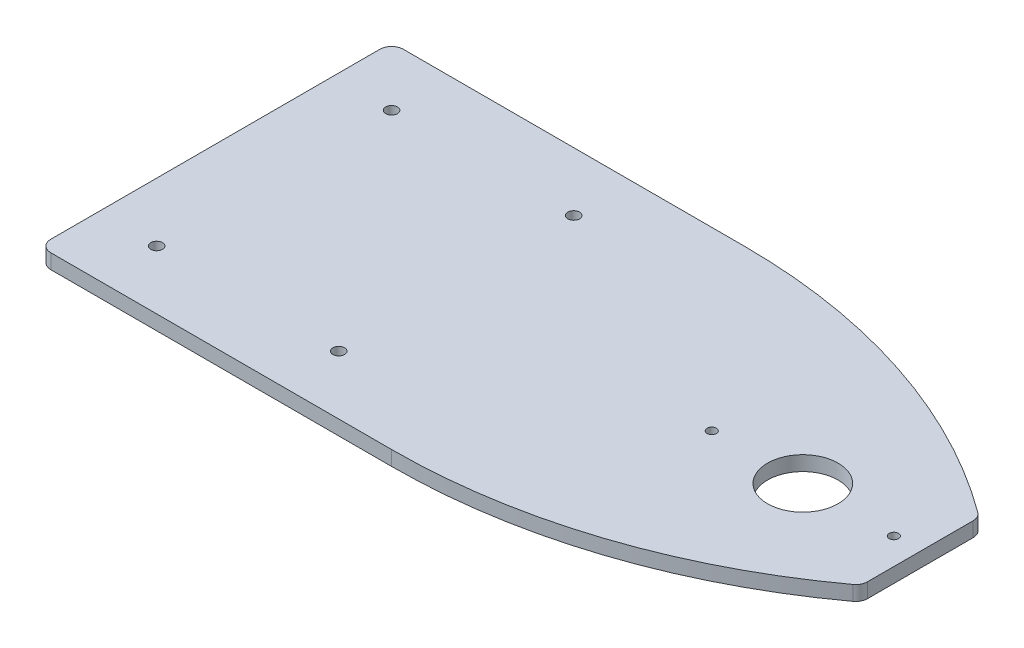
SolidWorks part; units mm, degrees
material "PLA"
ref_plane "Front" through (0, 0, 0) normal (0, 0, 1) x (1, 0, 0)
ref_plane "Top" through (0, 0, 0) normal (0, 1, 0) x (1, 0, 0)
ref_plane "Right" through (0, 0, 0) normal (1, 0, 0) x (0, 0, -1)
sketch "Sketch1" plane through (0, 0, 0) normal (0, 1, 0) x (1, 0, 0)
  line L1 (76.2, -38.1) -> (-76.2, -38.1)
  line L2 (76.2, -38.1) -> (76.2, 38.1)
  line L3 (76.2, 38.1) -> (-76.2, 38.1)
  line L4 (-76.2, -38.1) -> (-76.2, 38.1)
  line L5 (76.2, -38.1) -> (-76.2, 38.1) construction
  line L6 (76.2, 38.1) -> (-76.2, -38.1) construction
  point P0 (0, 0)
  dimension "D1" = 76.2
  dimension "D2" = 152.4
extrude "Boss-Extrude1" add sketch "Sketch1" along normal blind 3.175
sketch "Sketch4" plane through (0, 3.175, 0) normal (0, 1, 0) x (1, 0, 0)
  line L0 (0, 38.1) -> (76.2, 38.1)
  line L1 (76.2, 38.1) -> (-76.2, 38.1) construction
  line L2 (76.2, 38.1) -> (76.2, 12.7)
  line L3 (76.2, -38.1) -> (76.2, 38.1) construction
  line L4 (76.2, -38.1) -> (76.2, -12.7)
  line L5 (76.2, -38.1) -> (0, -38.1)
  line L6 (-76.2, -38.1) -> (76.2, -38.1) construction
  arc A0 (0, -38.1) -> (76.2, -12.7) centre (0, 88.9) ccw
  arc A1 (0, 38.1) -> (76.2, 12.7) centre (0, -88.9) cw
  dimension "D3" = 127
  dimension "D4" = 127
  dimension "D1" = 25.4
  dimension "D2" = 25.4
extrude "Cut-Extrude1" cut sketch "Sketch4" against normal blind 3.175
fillet "Fillet2" radius 2.54 2 edges at (76.2, 1.5875, 12.7) (76.2, 1.5875, -12.7)
fillet "Fillet3" radius 2.54 2 edges at (-76.2, 1.5875, 38.1) (-76.2, 1.5875, -38.1)
sketch "Sketch5" plane through (0, 3.175, 0) normal (0, 1, 0) x (1, 0, 0)
  line L0 (-55, 0) -> (55, 0) construction
  line L1 (76.2, -11.422) -> (76.2, 11.422) construction
  circle A0 centre (50.8, 0) radius 7.62
  dimension "D1" = 15.24
  dimension "D2" = 25.4
extrude "Cut-Extrude2" cut sketch "Sketch5" against normal blind 3.175
sketch "Sketch6" plane through (0, 3.175, 0) normal (0, 1, 0) x (1, 0, 0)
  line L0 (0, 38.1) -> (-73.66, 38.1) construction
  line L1 (-73.66, -38.1) -> (0, -38.1) construction
  line L2 (-76.2, 35.56) -> (-76.2, -35.56) construction
  circle A0 centre (-63.5, 25.4) radius 1.27
  circle A1 centre (-63.5, -25.4) radius 1.27
  circle A2 centre (-24.13, 25.4) radius 1.27
  circle A3 centre (-24.13, -25.4) radius 1.27
  dimension "D1" = 2.54
  dimension "D2" = 2.54
  dimension "D4" = 12.7
  dimension "D7" = 2.54
  dimension "D8" = 2.54
  dimension "D3" = 12.7
  dimension "D5" = 12.7
  dimension "D6" = 12.7
  dimension "D9" = 39.37
  dimension "D10" = 39.37
extrude "Cut-Extrude3" cut sketch "Sketch6" against normal blind 3.175
sketch "Sketch7" plane through (0, 3.175, 0) normal (0, 1, 0) x (1, 0, 0)
  line L0 (50.8, -7.62) -> (50.8, 7.62)
  line L1 (50.8, 0) -> (70.485, 0)
  line L2 (-1.7463, 0) -> (1.7463, 0) construction
  line L3 (50.8, 0) -> (31.115, 0)
  circle A0 centre (50.8, 0) radius 7.62 construction
  circle A1 centre (70.485, 0) radius 1.0033
  circle A2 centre (31.115, 0) radius 1.0033
  dimension "D3" = 2.0066
  dimension "D4" = 2.0066
  dimension "D1" = 19.685
  dimension "D2" = 19.685
extrude "Cut-Extrude4" cut sketch "Sketch7" against normal through all
